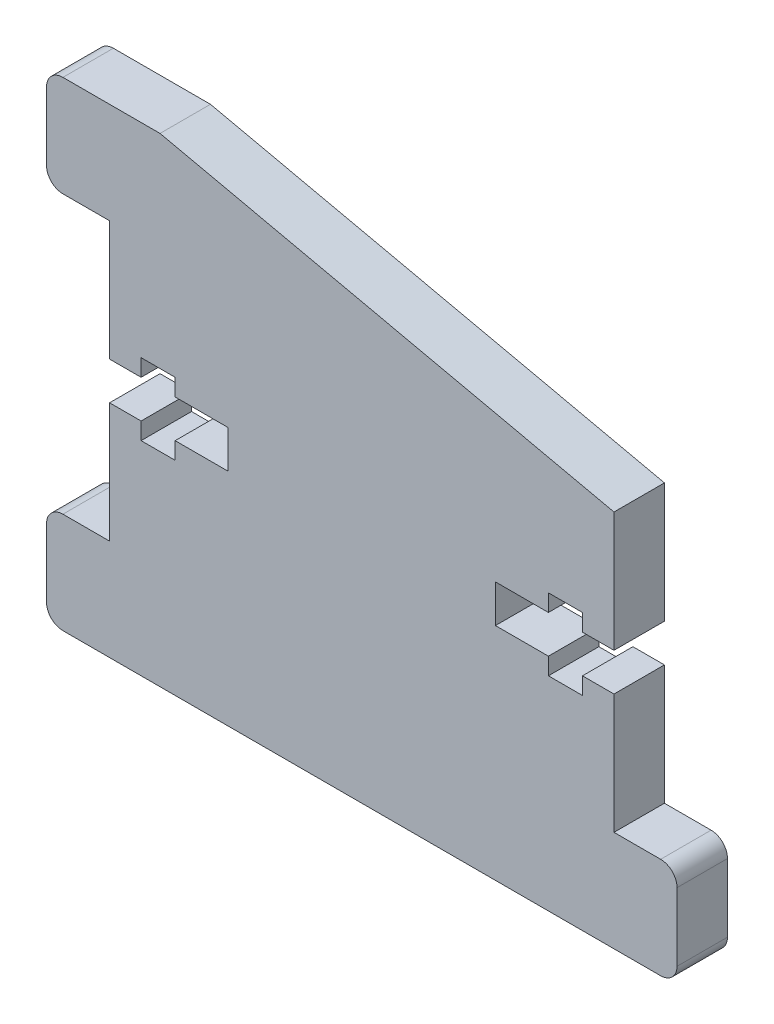
SolidWorks part; units mm, degrees
ref_plane "前视基准面" through (0, 0, 0) normal (0, 0, 1) x (1, 0, 0)
ref_plane "上视基准面" through (0, 0, 0) normal (0, 1, 0) x (1, 0, 0)
ref_plane "右视基准面" through (0, 0, 0) normal (1, 0, 0) x (0, 0, -1)
sketch "草图1" plane through (0, 0, 0) normal (0, 0, 1) x (1, 0, 0)
  line L0 (-33.5238, 29.5899) -> (-28.5238, 29.5899)
  line L1 (-33.5238, 29.5899) -> (-33.5238, 37.5899)
  line L2 (-33.5238, 37.5899) -> (-28.5238, 37.5899)
  line L3 (-28.5238, 37.5899) -> (-28.5238, 47.0899)
  line L4 (-28.5238, 47.0899) -> (-26.0238, 47.0899)
  line L5 (-26.0238, 47.0899) -> (-26.0238, 45.7399)
  line L6 (-26.0238, 45.7399) -> (-23.3238, 45.7399)
  line L7 (-23.3238, 45.7399) -> (-23.3238, 47.0899)
  line L8 (-23.3238, 47.0899) -> (-19.1238, 47.0899)
  line L9 (-19.1238, 47.0899) -> (-19.1238, 50.0899)
  line L10 (-19.1238, 50.0899) -> (-23.3238, 50.0899)
  line L11 (-23.3238, 50.0899) -> (-23.3238, 51.4399)
  line L12 (-23.3238, 51.4399) -> (-26.0238, 51.4399)
  line L13 (-26.0238, 51.4399) -> (-26.0238, 50.0899)
  line L14 (-26.0238, 50.0899) -> (-28.5238, 50.0899)
  line L15 (-28.5238, 59.5899) -> (-28.5238, 50.0899)
  line L16 (-19.1238, 48.5899) -> (-21.8238, 48.5899) construction
  line L17 (-33.5238, 59.5899) -> (-28.5238, 59.5899)
  line L18 (-33.5238, 67.5899) -> (-33.5238, 59.5899)
  line L19 (-33.5238, 67.5899) -> (-28.5238, 67.5899)
  line L20 (-28.5238, 29.5899) -> (11.4762, 29.5899)
  line L21 (-8.5238, 29.5899) -> (-8.5238, 32.8335) construction
  line L22 (11.4762, 59.5899) -> (11.4762, 50.0899)
  line L23 (2.0762, 48.5899) -> (4.7762, 48.5899) construction
  line L24 (8.9762, 50.0899) -> (11.4762, 50.0899)
  line L25 (8.9762, 51.4399) -> (8.9762, 50.0899)
  line L26 (6.2762, 51.4399) -> (8.9762, 51.4399)
  line L27 (6.2762, 50.0899) -> (6.2762, 51.4399)
  line L28 (2.0762, 50.0899) -> (6.2762, 50.0899)
  line L29 (2.0762, 47.0899) -> (2.0762, 50.0899)
  line L30 (6.2762, 47.0899) -> (2.0762, 47.0899)
  line L31 (6.2762, 45.7399) -> (6.2762, 47.0899)
  line L32 (8.9762, 45.7399) -> (6.2762, 45.7399)
  line L33 (8.9762, 47.0899) -> (8.9762, 45.7399)
  line L34 (11.4762, 47.0899) -> (8.9762, 47.0899)
  line L35 (11.4762, 37.5899) -> (11.4762, 47.0899)
  line L36 (16.4762, 37.5899) -> (11.4762, 37.5899)
  line L37 (16.4762, 29.5899) -> (16.4762, 37.5899)
  line L38 (16.4762, 29.5899) -> (11.4762, 29.5899)
  line L39 (11.4762, 59.5899) -> (-24.5238, 67.5899)
  line L40 (-24.5238, 67.5899) -> (-28.5238, 67.5899)
  dimension "D1" = 2.7
  dimension "D2" = 3
  dimension "D3" = 1.35
  dimension "D4" = 9.5
  dimension "D5" = 5
  dimension "D6" = 8
  dimension "D7" = 40
  dimension "D8" = 2.5
  dimension "D9" = 4.2
extrude "凸台-拉伸1" add sketch "草图1" along normal blind 4
sketch "草图2" plane through (-28.5238, 0, 0) normal (-1, 0, 0) x (0, 0, 1)
  line L0 (2, 50.0899) -> (2, 47.0899) construction
  line L1 (4, 50.0899) -> (0, 50.0899) construction
  line L2 (4, 47.0899) -> (0, 47.0899) construction
  circle A0 centre (2, 48.5899) radius 1.5
fillet "圆角1" radius 1.3 6 edges at (16.4762, 37.5899, 2) (16.4762, 29.5899, 2) (-33.5238, 67.5899, 2) (-33.5238, 59.5899, 2) (-33.5238, 37.5899, 2) (-33.5238, 29.5899, 2)
